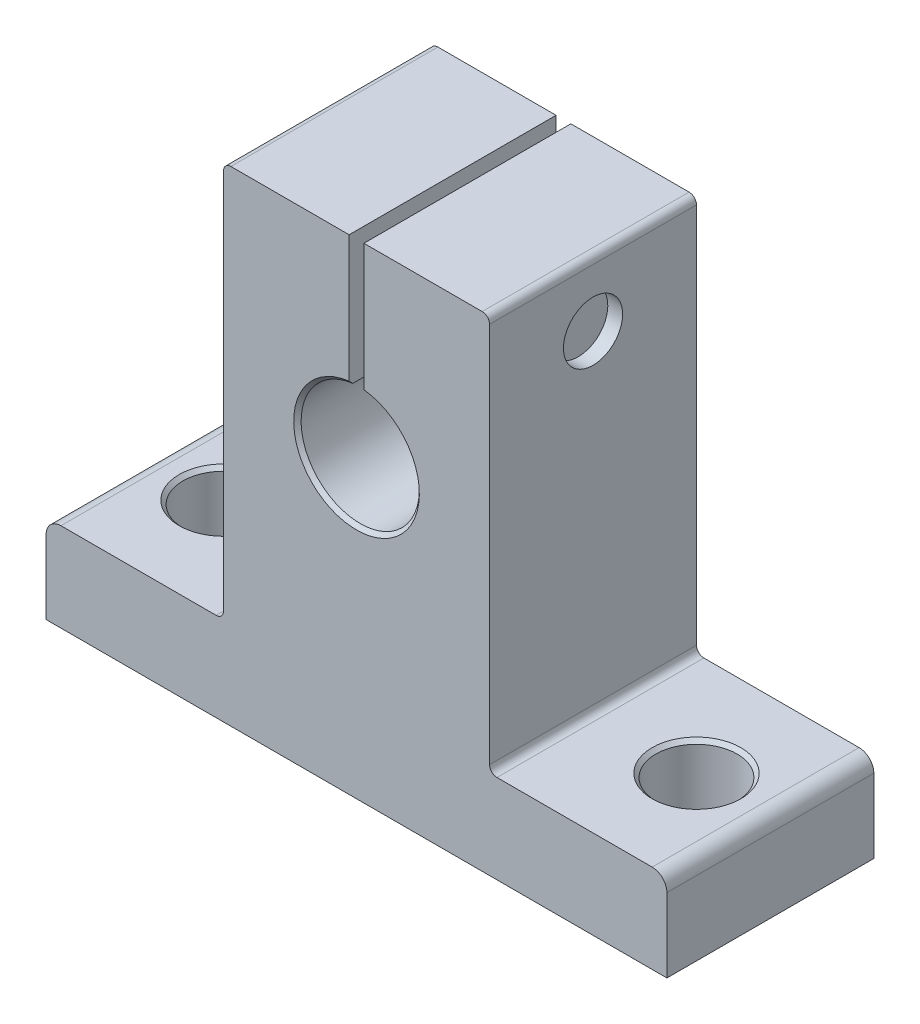
SolidWorks part; units mm, degrees
ref_plane "Front Plane" through (0, 0, 0) normal (0, 0, 1) x (1, 0, 0)
ref_plane "Top Plane" through (0, 0, 0) normal (0, 1, 0) x (1, 0, 0)
ref_plane "Right Plane" through (0, 0, 0) normal (1, 0, 0) x (0, 0, -1)
sketch "Sketch1" plane through (0, 0, 0) normal (0, 0, 1) x (1, 0, 0)
  line L0 (-21, 0) -> (21, 0)
  line L1 (-21, 0) -> (-21, 6)
  line L2 (-21, 6) -> (-9, 6)
  line L3 (-9, 6) -> (-9, 32.8)
  line L4 (-9, 32.8) -> (-0.5, 32.8)
  line L5 (9, 32.8) -> (9, 6)
  line L6 (9, 6) -> (21, 6)
  line L7 (21, 6) -> (21, 0)
  line L8 (-0.5, 32.8) -> (-0.5, 23.9686)
  line L9 (0.5, 32.8) -> (0.5, 23.9686)
  line L10 (0.5, 32.8) -> (9, 32.8)
  arc A0 (-0.5, 23.9686) -> (0.5, 23.9686) centre (0, 20) ccw
  point P11 (0, 0)
  point P13 (-0.5, 28.3843)
  dimension "D6" = 4
  dimension "D1" = 42
  dimension "D2" = 6
  dimension "D3" = 20
  dimension "D4" = 32.8
  dimension "D5" = 1
  dimension "D7" = 18
extrude "Boss-Extrude1" add sketch "Sketch1" along normal blind 14
sketch "Sketch3" plane through (0, 0, 0) normal (0, -1, 0) x (1, 0, 0)
  line L0 (-16, 7) -> (16, 7) construction
  line L1 (-21, 14) -> (-21, 0) construction
  circle A0 centre (-16, 7) radius 2.75
  circle A1 centre (16, 7) radius 2.75
  point P2 (0, 7)
  point P7 (-21, 7)
  dimension "D2" = 5.5
  dimension "D1" = 32
extrude "Cut-Extrude1" cut sketch "Sketch3" against normal blind 6 and the other way through all
fillet "Fillet1" radius 1 2 edges at (21, 6, 7) (-21, 6, 7)
fillet "Fillet2" radius 0.5 4 edges at (-9, 32.8, 7) (9, 32.8, 7) (9, 6, 7) (-9, 6, 7)
chamfer "Chamfer1" distance 0.25 6 edges at (-16, 0, 9.75) (16, 0, 9.75) (18.75, 6, 7) (-13.25, 6, 7) (0, 16, 0) (0, 16, 14)
sketch "Sketch4" plane through (-9, 0, 0) normal (-1, 0, 0) x (0, 0, 1)
  line L0 (14, 32.3) -> (0, 32.3) construction
  line L1 (0, 32.8) -> (14, 32.8) construction
  circle A0 centre (7, 28.4) radius 3.1
  point P6 (7, 32.3)
  dimension "D1" = 6.2
  dimension "D2" = 4.4
extrude "Cut-Extrude2" cut sketch "Sketch4" against normal blind 1
sketch "Sketch5" plane through (-8, 0, 0) normal (-1, 0, 0) x (0, 0, 1)
  circle A0 centre (7, 28.4) radius 3.1
  circle A1 centre (7, 28.4) radius 3
  dimension "D1" = 6
  dimension "D2" = 6.2
extrude "Cut-Extrude3" cut sketch "Sketch5" against normal blind 4
chamfer "Chamfer2" distance 0.2 1 edges at (-8, 25.4, 7)
sketch "Sketch6" plane through (-8, 0, 0) normal (-1, 0, 0) x (0, 0, 1)
  line L1 (7.1608, 30.1246) -> (5.5869, 29.4015)
  line L2 (5.5869, 29.4015) -> (5.4261, 27.6769)
  line L3 (5.4261, 27.6769) -> (6.8392, 26.6754)
  line L4 (6.8392, 26.6754) -> (8.4131, 27.3985)
  line L5 (8.4131, 27.3985) -> (8.5739, 29.1231)
  line L6 (8.5739, 29.1231) -> (7.1608, 30.1246)
  circle A0 centre (7, 28.4) radius 1.5 construction
  dimension "D1" = 3
extrude "Cut-Extrude4" cut sketch "Sketch6" against normal blind 2
sketch "Sketch7" plane through (-0.5, 0, 0) normal (1, 0, 0) x (0, 0, -1)
  circle A0 centre (-7, 28.4) radius 2
  dimension "D1" = 4
extrude "Boss-Extrude2" add sketch "Sketch7" along normal blind 1
sketch "Sketch8" plane through (9, 0, 0) normal (1, 0, 0) x (0, 0, -1)
  circle A0 centre (-7, 28.4) radius 2
  dimension "D1" = 4
extrude "Cut-Extrude5" cut sketch "Sketch8" against normal blind 1
sketch "Sketch9" plane through (-8, 0, 0) normal (-1, 0, 0) x (0, 0, 1)
  circle A0 centre (7, 28.4) radius 1.7321
extrude "Cut-Extrude6" cut sketch "Sketch9" against normal blind 1 draft 45
equation "\"h\"= 20'6"
equation "\"w\"= 42'1"
equation "\"l\"= 14'3"
equation "\"f\"= 32.8'2"
equation "\"g\"= 6'9"
equation "\"p\"= 18'5"
equation "\"b\"= 32'4"
equation "\"s\"= 5.5'10"
equation "\"sk\"= 8'7 dg kinh truc"
equation "\"D1@Sketch1\"=\"w\""
equation "\"D2@Sketch1\"=\"g\""
equation "\"D3@Sketch1\"=\"h\""
equation "\"D4@Sketch1\"=\"f\""
equation "\"rk\"= 1'11 be rong khe"
equation "\"D5@Sketch1\"=\"rk\""
equation "\"D6@Sketch1\"=\"sk\"/2"
equation "\"D1@Boss-Extrude1\"=\"l\""
equation "\"D1@Sketch3\"=\"b\""
equation "\"D2@Sketch3\"=\"s\""
equation "\"D1@Cut-Extrude1\"=\"g\""
equation "\"D7@Sketch1\"=\"p\""
equation "\"bo\"= 1'12 bo goc"
equation "\"D1@Fillet1\"=\"bo\""
equation "\"D1@Fillet2\"=\"bo\"/2"
equation "\"D1@Chamfer1\"=\"bo\"/4"
equation "\"m\"= 4'8 bu long"
equation "\"D1@Sketch4\"=1.5*\"m\"+0.2"
equation "\"D1@Sketch5\"=\"m\"*1.5"
equation "\"D2@Sketch5\"=\"m\"*1.5+0.2"
equation "\"D1@Cut-Extrude3\"=\"m\""
equation "\"D1@Chamfer2\"=\"m\"*0.05"
equation "\"D1@Cut-Extrude4\"=\"m\"/2"
equation "\"D1@Sketch6\"=\"m\"*3/4"
equation "\"D1@Sketch7\"=\"m\""
equation "\"D1@Boss-Extrude2\"=\"rk\""
equation "\"D1@Sketch8\"=\"m\""
equation "\"D2@Sketch4\"=(\"f\"-\"h\"-\"sk\"/2)/2"
